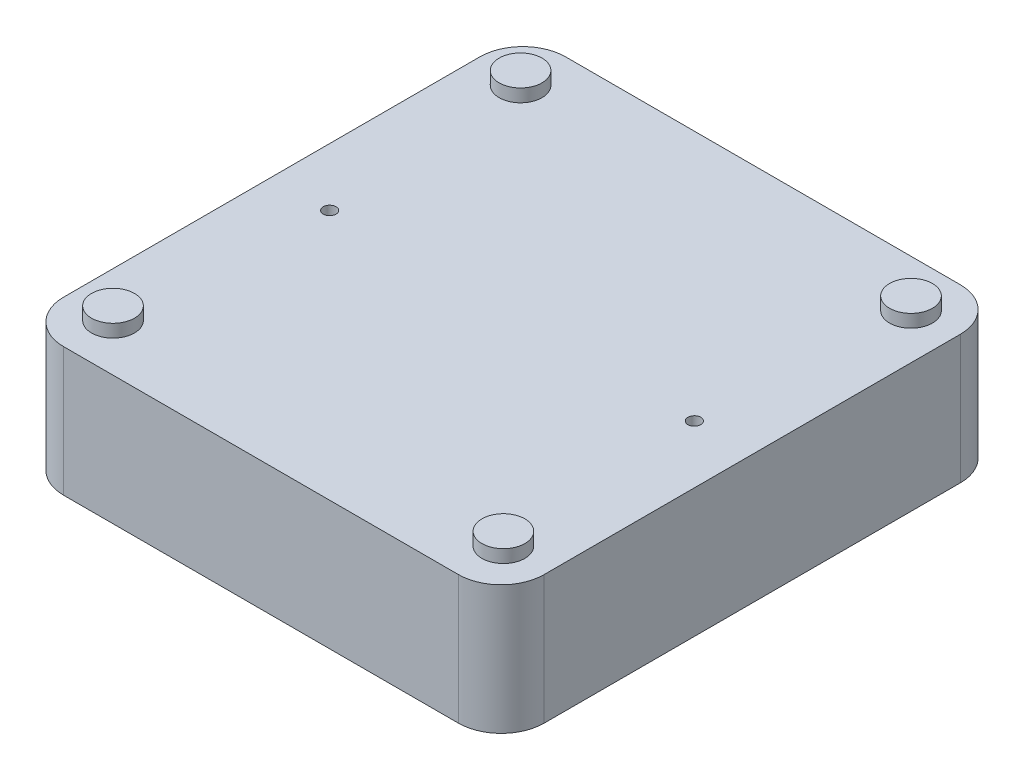
SolidWorks part; units mm, degrees
ref_plane "前视基准面" through (0, 0, 0) normal (0, 0, 1) x (1, 0, 0)
ref_plane "上视基准面" through (0, 0, 0) normal (0, 1, 0) x (1, 0, 0)
ref_plane "右视基准面" through (0, 0, 0) normal (1, 0, 0) x (0, 0, -1)
sketch "草图1" plane through (0, 0, 0) normal (0, 1, 0) x (1, 0, 0)
  line L1 (-56, -58.5) -> (56, -58.5)
  line L2 (-56, -58.5) -> (-56, 58.5)
  line L3 (-56, 58.5) -> (56, 58.5)
  line L4 (56, -58.5) -> (56, 58.5)
  line L5 (-56, -58.5) -> (56, 58.5) construction
  line L6 (-56, 58.5) -> (56, -58.5) construction
  point P0 (0, 0)
  dimension "D1" = 112
  dimension "D2" = 117
extrude "凸台-拉伸1" add sketch "草图1" along normal blind 30
fillet "圆角1" radius 10 4 edges at (-56, 15, -58.5) (-56, 15, 58.5) (56, 15, -58.5) (56, 15, 58.5)
sketch "草图2" plane through (0, 30, 0) normal (0, 1, 0) x (1, 0, 0)
  line L1 (-45.5, 47.5) -> (45.5, 47.5) construction
  line L2 (-45.5, 47.5) -> (-45.5, -47.5) construction
  line L3 (-45.5, -47.5) -> (45.5, -47.5) construction
  line L4 (45.5, 47.5) -> (45.5, -47.5) construction
  line L5 (-45.5, 47.5) -> (45.5, -47.5) construction
  line L6 (-45.5, -47.5) -> (45.5, 47.5) construction
  circle A4 centre (-45.5, 47.5) radius 5
  circle A5 centre (45.5, 47.5) radius 5
  circle A6 centre (-45.5, -47.5) radius 5
  circle A7 centre (45.5, -47.5) radius 5
  point P0 (0, 0)
  dimension "D1" = 91
  dimension "D3" = 10
  dimension "D2" = 95
extrude "凸台-拉伸2" add sketch "草图2" along normal blind 3
sketch "草图3" plane through (0, 30, 0) normal (0, 1, 0) x (1, 0, 0)
  line L0 (-42.5, 0) -> (42.5, 0) construction
  circle A0 centre (-42.5, 0) radius 1.5
  circle A1 centre (42.5, 0) radius 1.5
  point P2 (0, 0)
  dimension "D2" = 3
  dimension "D1" = 85
extrude "切除-拉伸1" cut sketch "草图3" against normal blind 5
